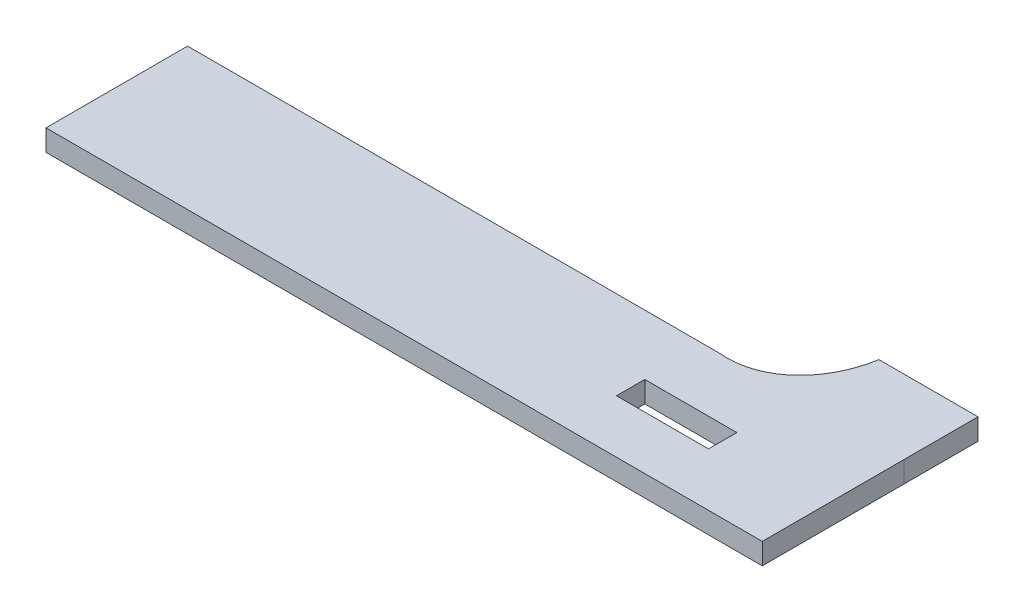
SolidWorks part; units mm, degrees
material "ABS"
ref_plane "前视基准面" through (0, 0, 0) normal (0, 0, 1) x (1, 0, 0)
ref_plane "上视基准面" through (0, 0, 0) normal (0, 1, 0) x (1, 0, 0)
ref_plane "右视基准面" through (0, 0, 0) normal (1, 0, 0) x (0, 0, -1)
other "Configuration Table"
sketch "草图2" plane through (0, 0, 0) normal (0, 1, 0) x (1, 0, 0)
  line L0 (-57.2675, 10.3818) -> (17.7325, 10.3818) construction
  line L1 (-57.2675, 10.3818) -> (43.9225, 10.3818)
  line L2 (-57.2675, 10.3818) -> (-57.2675, -9.6182)
  line L3 (-57.2675, -9.6182) -> (43.9225, -9.6182)
  line L4 (43.9225, 10.3818) -> (43.9225, -9.6182)
  line L5 (17.7325, 10.3818) -> (29.9212, 10.3818) construction
  line L6 (29.9212, 10.3818) -> (29.9212, 20.8624) construction
  line L7 (29.9212, 20.8624) -> (43.9212, 20.8624)
  line L8 (43.9212, 20.8624) -> (43.9225, 10.3818)
  spline S0 degree 3 poles (17.7325, 10.3818) (24.777, 9.6929) (29.0309, 15.2027) (29.9212, 20.8624) knots 0 0 0 0 1 1 1 1
  dimension "D1" = 101.19
  dimension "D2" = 20
extrude "凸台-拉伸1" add sketch "草图2" along normal blind 3 contours S0 L1 L2 L3 L4 | S0 L1 L8 L7
sketch "草图4" plane through (0, 3, 0) normal (0, 1, 0) x (1, 0, 0)
  line L1 (15.8126, 1.899) -> (28.8126, 1.899)
  line L2 (15.8126, 1.899) -> (15.8126, -2.101)
  line L3 (15.8126, -2.101) -> (28.8126, -2.101)
  line L4 (28.8126, 1.899) -> (28.8126, -2.101)
  dimension "D1" = 4
  dimension "D2" = 13
extrude "切除-拉伸1" cut sketch "草图4" against normal through all
